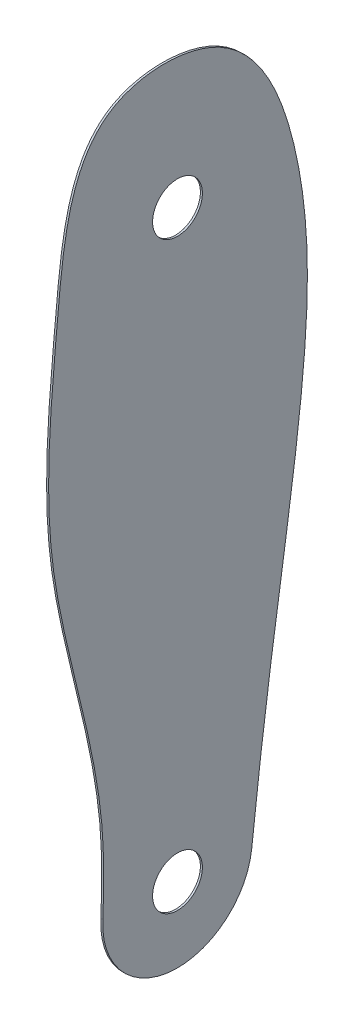
SolidWorks part; units mm, degrees
material "Teras S325"
ref_plane "Front Plane" through (0, 0, 0) normal (0, 0, 1) x (1, 0, 0)
ref_plane "Top Plane" through (0, 0, 0) normal (0, 1, 0) x (1, 0, 0)
ref_plane "Right Plane" through (0, 0, 0) normal (1, 0, 0) x (0, 0, -1)
sketch "Sketch5" plane through (0, 0, 0) normal (1, 0, 0) x (0, 0, -1)
  line L0 (0, 55) -> (0, -55) construction
  line L1 (55, 0) -> (-55, 0) construction
  line L2 (0, 0) -> (0, -293) construction
  arc A0 (-37.4333, -290.7645) -> (37.2779, -297.0755) centre (0, -293) ccw
  circle A1 centre (0, -293) radius 12.5
  circle A2 centre (0, 0) radius 12.5
  spline S0 degree 3 poles (37.2779, -297.0755) (40.2841, -269.578) (48.3744, -206.9029) (64.6436, -109.5045) (68.2091, -15.6662) (34.6363, 68.1237) (-52.0626, 67.1808) (-61.3628, -30.5674) (-70.9282, -131.0557) (-35.698, -222.6092) (-37.0848, -278.9991) (-37.4333, -290.7645) knots 0 0 0 0 0.106321 0.242883 0.375995 0.475519 0.539537 0.64184 0.780821 0.952014 0.997142 0.997142 0.997142 0.997142
  dimension "D1" = 75
  dimension "D2" = 25
  dimension "D3" = 293
  dimension "D4" = 25
extrude "Extrude1" add sketch "Sketch5" along normal mid plane 1
